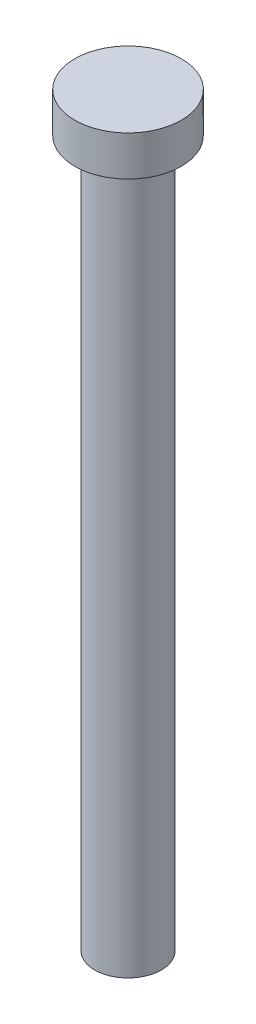
SolidWorks part; units mm, degrees
ref_plane "Front Plane" through (0, 0, 0) normal (0, 0, 1) x (1, 0, 0)
ref_plane "Top Plane" through (0, 0, 0) normal (0, 1, 0) x (1, 0, 0)
ref_plane "Right Plane" through (0, 0, 0) normal (1, 0, 0) x (0, 0, -1)
sketch "Sketch1" plane through (0, 0, 0) normal (0, 1, 0) x (1, 0, 0)
  circle A0 centre (0, 0) radius 3.175
  dimension "D1" = 6.35
extrude "Boss-Extrude1" add sketch "Sketch1" along normal blind 67.31
sketch "Sketch2" plane through (0, 67.31, 0) normal (0, 1, 0) x (1, 0, 0)
  circle A0 centre (0, 0) radius 5.08
extrude "Boss-Extrude2" add sketch "Sketch2" along normal blind 3.81
